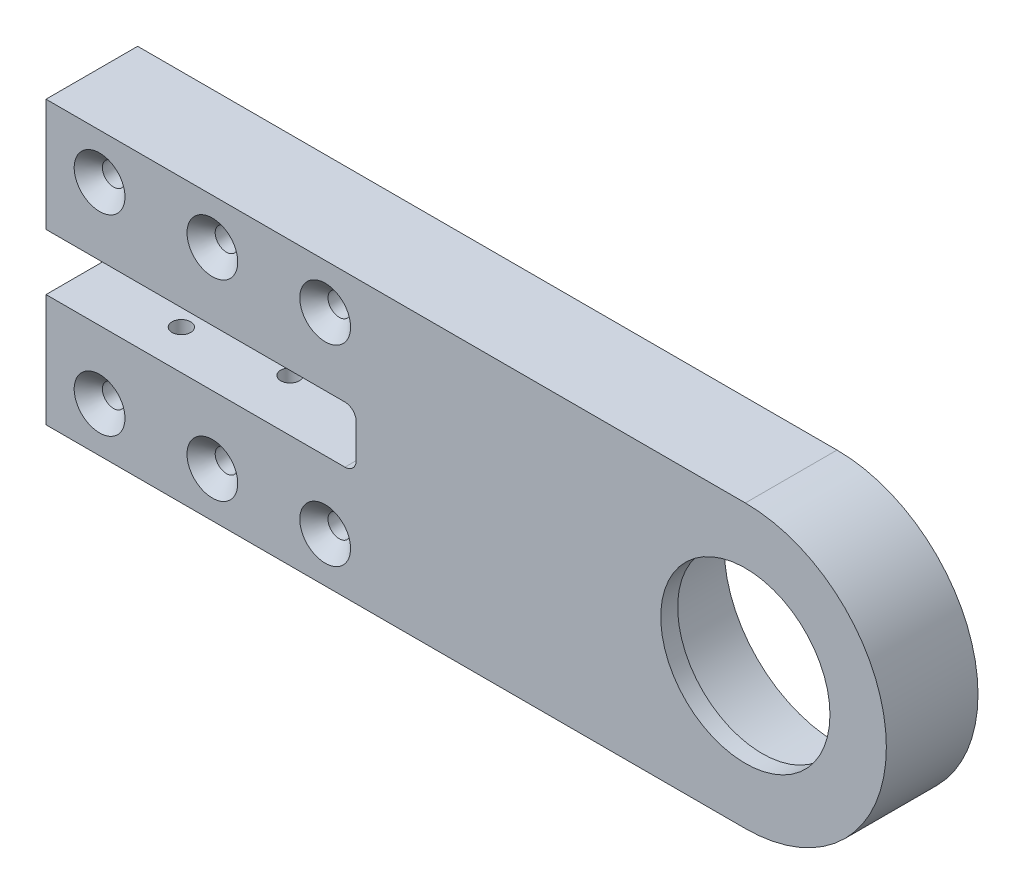
SolidWorks part; units mm, degrees
material "AISI 316 Stainless Steel Sheet (SS)"
ref_plane "Front Plane" through (0, 0, 0) normal (0, 0, 1) x (1, 0, 0)
ref_plane "Top Plane" through (0, 0, 0) normal (0, 1, 0) x (1, 0, 0)
ref_plane "Right Plane" through (0, 0, 0) normal (1, 0, 0) x (0, 0, -1)
sketch "Sketch1" plane through (0, 0, 0) normal (0, 0, 1) x (1, 0, 0)
  line L0 (-62, 5) -> (-9, 5)
  line L1 (-62, -25) -> (62, -25)
  line L2 (-62, -25) -> (-62, -5)
  line L3 (-62, 25) -> (62, 25)
  line L5 (-62, -25) -> (0, 0) construction
  line L6 (-62, 25) -> (0, 0) construction
  line L7 (-7, 3) -> (-7, -3)
  line L8 (-9, -5) -> (-62, -5)
  line L9 (-62, 5) -> (-62, 25)
  arc A0 (-7, -3) -> (-9, -5) centre (-9, -3) cw
  arc A1 (-7, 3) -> (-9, 5) centre (-9, 3) ccw
  arc A2 (62, -25) -> (62, 25) centre (62, 0) ccw
  circle A3 centre (62, 0) radius 20
  circle A4 centre (-52.5, 17) radius 2
  circle A5 centre (-32.5, 17) radius 2
  circle A6 centre (-12.5, 17) radius 2
  circle A7 centre (-32.5, -17) radius 2
  circle A8 centre (-12.5, -17) radius 2
  circle A9 centre (-52.5, -17) radius 2
  point P0 (0, 0)
  dimension "D5" = 2
  dimension "D7" = 40
  dimension "D8" = 4
  dimension "D1" = 124
  dimension "D2" = 50
  dimension "D3" = 20
  dimension "D4" = 20
  dimension "D6" = 53
  dimension "D9" = 9.5
  dimension "D10" = 8
  dimension "D11" = 3
  dimension "D12" = 2
extrude "Boss-Extrude1" add sketch "Sketch1" along normal blind 16.25
sketch "Sketch2" plane through (0, 0, 16.25) normal (0, 0, 1) x (1, 0, 0)
  circle A0 centre (62, 0) radius 15
  circle A1 centre (62, 0) radius 20 construction
  circle A2 centre (62, 0) radius 20
  dimension "D1" = 30
extrude "Boss-Extrude2" add sketch "Sketch2" against normal blind 3
hole_wizard "CSK for M5 Flat Head Machine Screw1" positions "Sketch5" profile "Sketch6" countersink size "M5" standard "ANSI Metric" end condition through all
sketch "Sketch5" plane through (0, 0, 16.25) normal (0, 0, 1) x (1, 0, 0)
  point P0 (-52.5, 17)
  point P3 (-32.5, 17)
  point P6 (-12.5, 17)
  point P9 (-52.5, -17)
  point P12 (-32.5, -17)
  point P15 (-12.5, -17)
sketch "Sketch6" plane through (-52.5, 17, 16.25) normal (1, 0, 0) x (0, -1, 0)
  line L0 (0, 0) -> (0, 16.25)
  line L1 (0, 16.25) -> (2, 16.25)
  line L2 (2, 16.25) -> (2, 2.5)
  line L3 (2, 2.5) -> (4.5, 0)
  line L5 (4.5, 0) -> (0, 0)
  line L6 (-2, 2.5) -> (-4.5, 0) construction
  line L11 (0, -6.35) -> (0, 107.95) construction
  dimension "Thru Hole Dia." = 4
  dimension "Thru Hole Depth" = 16.25
  dimension "Near C'Sink Dia." = 9
  dimension "Near C'Sink Angle" = 90
sketch "Sketch7" plane through (0, -25, 0) normal (0, -1, 0) x (1, 0, 0)
  line L0 (-62, 16.25) -> (-62, 0) construction
  line L1 (-62, 16.25) -> (62, 16.25) construction
  circle A0 centre (-45, 9.25) radius 1.65
  circle A1 centre (-27.9436, 7.0321) radius 1.65
  dimension "D1" = 3.3
  dimension "D2" = 17
  dimension "D5" = 3.3
  dimension "D3" = 17.2
  dimension "D4" = 7
extrude "Cut-Extrude1" cut sketch "Sketch7" against normal up to next
